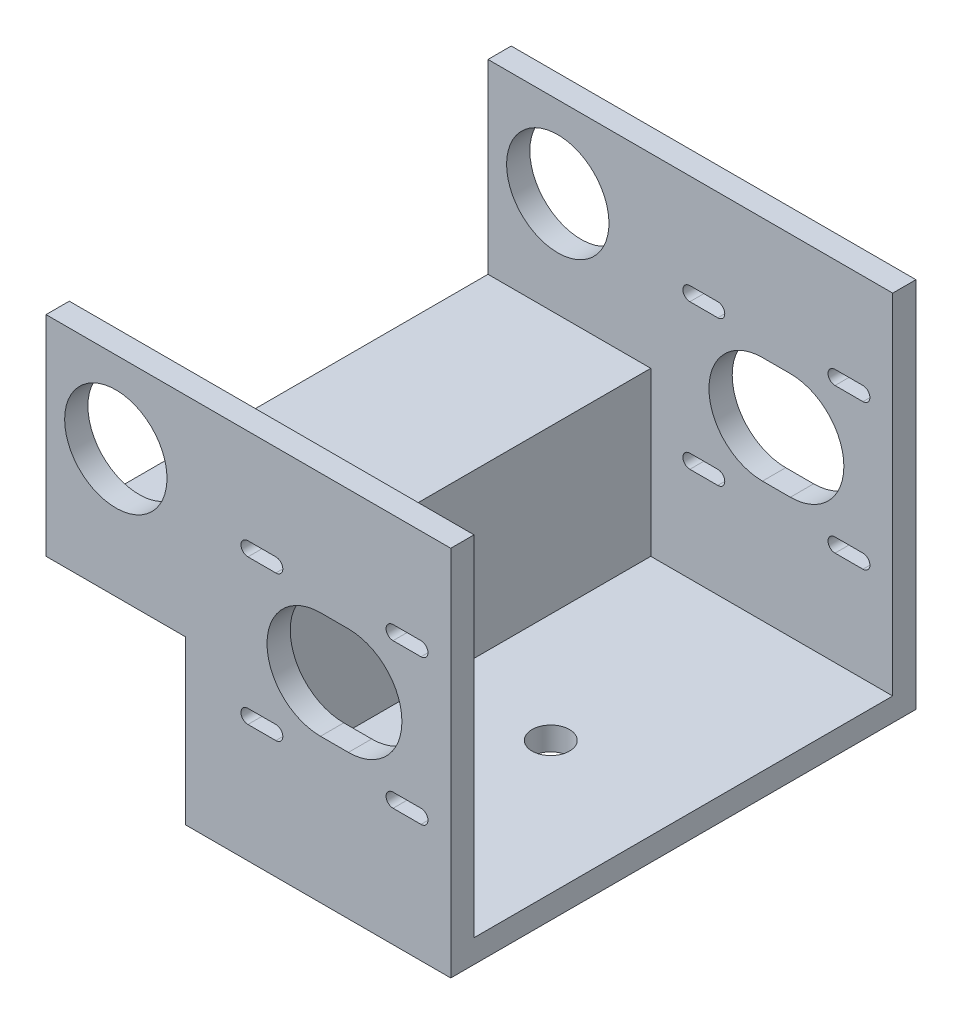
SolidWorks part; units mm, degrees
ref_plane "Front Plane" through (0, 0, 0) normal (0, 0, 1) x (1, 0, 0)
ref_plane "Top Plane" through (0, 0, 0) normal (0, 1, 0) x (1, 0, 0)
ref_plane "Right Plane" through (0, 0, 0) normal (1, 0, 0) x (0, 0, -1)
sketch "Sketch1" plane through (0, 0, 0) normal (0, 1, 0) x (1, 0, 0)
  line L1 (-28.5, 50) -> (28.5, 50)
  line L2 (-28.5, 50) -> (-28.5, -50)
  line L3 (-28.5, -50) -> (28.5, -50)
  line L4 (28.5, 50) -> (28.5, -50)
  line L5 (-28.5, 50) -> (28.5, -50) construction
  line L6 (-28.5, -50) -> (28.5, 50) construction
  point P0 (0, 0)
  dimension "D1" = 100
  dimension "D2" = 57
extrude "Boss-Extrude1" add sketch "Sketch1" along normal blind 80
sketch "Sketch3" plane through (28.5, 40, 0) normal (-1, 0, 0) x (0, 1, 0)
  line L1 (40, 45) -> (-35, 45)
  line L2 (40, 45) -> (40, -45)
  line L3 (40, -45) -> (-35, -45)
  line L4 (-35, 45) -> (-35, -45)
  line L5 (40, 45) -> (-35, -45) construction
  line L6 (40, -45) -> (-35, 45) construction
  line L10 (40, -50) -> (40, 50) construction
  line L11 (-40, -50) -> (-40, 50) construction
  line L12 (40, 50) -> (-40, 50) construction
  line L13 (40, -50) -> (-40, -50) construction
  point P0 (2.5, 0)
  dimension "D1" = 5
  dimension "D2" = 5
  dimension "D3" = 5
extrude "Cut-Extrude1" cut sketch "Sketch3" along normal blind 52
sketch "Sketch4" plane through (-40, 5, 0) normal (0, -1, 0) x (-1, 0, 0)
  line L0 (-40, 0) -> (-40, 10) construction
  circle A0 centre (-40, 0) radius 4.025
  circle A1 centre (-40, 10) radius 1.5 construction
  circle A2 centre (-30, 0) radius 1.5 construction
  circle A3 centre (-40, -10) radius 1.5 construction
  circle A4 centre (-50, 0) radius 1.5 construction
  dimension "D1" = 8.05
  dimension "D2" = 3
  dimension "D3" = 10
  dimension "D4" = 4
extrude "Cut-Extrude2" cut sketch "Sketch4" along normal through all
sketch "Sketch7" plane through (-28.5, 0, 0) normal (-1, 0, 0) x (0, 0, 1)
  line L0 (50, 80) -> (50, 0) construction
  line L1 (-50, 80) -> (-45, 80)
  line L2 (-50, 80) -> (-50, 35)
  line L4 (-45, 80) -> (-45, 40)
  line L5 (50, 80) -> (45, 80)
  line L6 (50, 80) -> (50, 35)
  line L8 (45, 80) -> (45, 40)
  line L9 (-50, 80) -> (50, 80) construction
  line L11 (-45, 40) -> (45, 40)
  line L13 (-50, 35) -> (50, 35)
  dimension "D1" = 5
  dimension "D2" = 40
  dimension "D3" = 5
extrude "Boss-Extrude2" add sketch "Sketch7" along normal blind 30
sketch "Sketch8" plane through (-28.5, 0, 0) normal (-1, 0, 0) x (0, 0, 1)
  line L4 (-45, 80) -> (-45, 40)
  line L5 (-45, 40) -> (45, 40)
  line L6 (45, 40) -> (45, 80)
  line L7 (45, 80) -> (-45, 80)
  line L8 (-45, 80) -> (-45, 40)
  line L9 (-45, 40) -> (45, 40)
  line L10 (45, 40) -> (45, 80)
  line L11 (45, 80) -> (-45, 80)
  dimension "D1" = 0
extrude "Cut-Extrude5" cut sketch "Sketch8" against normal up to next
sketch "Sketch5" plane through (0, 0, -50) normal (0, 0, -1) x (-1, 0, 0)
  line L0 (-3.5, 42.5) -> (31.0759, 42.5) construction
  line L1 (-3.5, 42.5) -> (-3.5, 17.143) construction
  line L2 (-28.5, 80) -> (58.5, 80) construction
  line L3 (-28.5, 80) -> (58.5, 80) construction
  line L4 (58.5, 80) -> (58.5, 35) construction
  line L5 (-22.1, 58.1) -> (-16.1, 58.1) construction
  line L6 (-22.1, 59.6) -> (-16.1, 59.6)
  line L7 (-22.1, 56.6) -> (-16.1, 56.6)
  line L8 (-28.5, 80) -> (-28.5, 0) construction
  line L9 (-0.5, 42.5) -> (-6.5, 42.5) construction
  line L10 (-0.5, 31) -> (-6.5, 31)
  line L11 (-0.5, 54) -> (-6.5, 54)
  line L12 (-22.1, 26.9) -> (-16.1, 26.9) construction
  line L13 (-22.1, 25.4) -> (-16.1, 25.4)
  line L14 (-22.1, 28.4) -> (-16.1, 28.4)
  line L15 (15.1, 26.9) -> (9.1, 26.9) construction
  line L16 (15.1, 25.4) -> (9.1, 25.4)
  line L17 (15.1, 28.4) -> (9.1, 28.4)
  line L18 (15.1, 58.1) -> (9.1, 58.1) construction
  line L19 (15.1, 59.6) -> (9.1, 59.6)
  line L20 (15.1, 56.6) -> (9.1, 56.6)
  circle A5 centre (43.5, 62.5) radius 11
  arc A7 (-22.1, 59.6) -> (-22.1, 56.6) centre (-22.1, 58.1) ccw
  arc A8 (-16.1, 56.6) -> (-16.1, 59.6) centre (-16.1, 58.1) ccw
  arc A9 (-0.5, 31) -> (-0.5, 54) centre (-0.5, 42.5) ccw
  arc A10 (-6.5, 54) -> (-6.5, 31) centre (-6.5, 42.5) ccw
  arc A11 (-22.1, 25.4) -> (-22.1, 28.4) centre (-22.1, 26.9) cw
  arc A12 (-16.1, 28.4) -> (-16.1, 25.4) centre (-16.1, 26.9) cw
  arc A13 (15.1, 25.4) -> (15.1, 28.4) centre (15.1, 26.9) ccw
  arc A14 (9.1, 28.4) -> (9.1, 25.4) centre (9.1, 26.9) ccw
  arc A15 (15.1, 59.6) -> (15.1, 56.6) centre (15.1, 58.1) cw
  arc A16 (9.1, 56.6) -> (9.1, 59.6) centre (9.1, 58.1) cw
  point P2 (-19.1, 58.1)
  point P8 (-19.1, 42.5)
  point P13 (-3.5, 42.5)
  point P31 (-19.1, 26.9)
  point P38 (12.1, 26.9)
  point P45 (12.1, 58.1)
  dimension "D5" = 15.6
  dimension "D8" = 6
  dimension "D9" = 22
  dimension "D2" = 1.5
  dimension "D7" = 11.5
  dimension "D12" = 25
  dimension "D3" = 15.6
  dimension "D4" = 6
  dimension "D6" = 37.5
  dimension "D10" = 17.5
  dimension "D11" = 15
extrude "Cut-Extrude3" cut sketch "Sketch5" against normal through all
